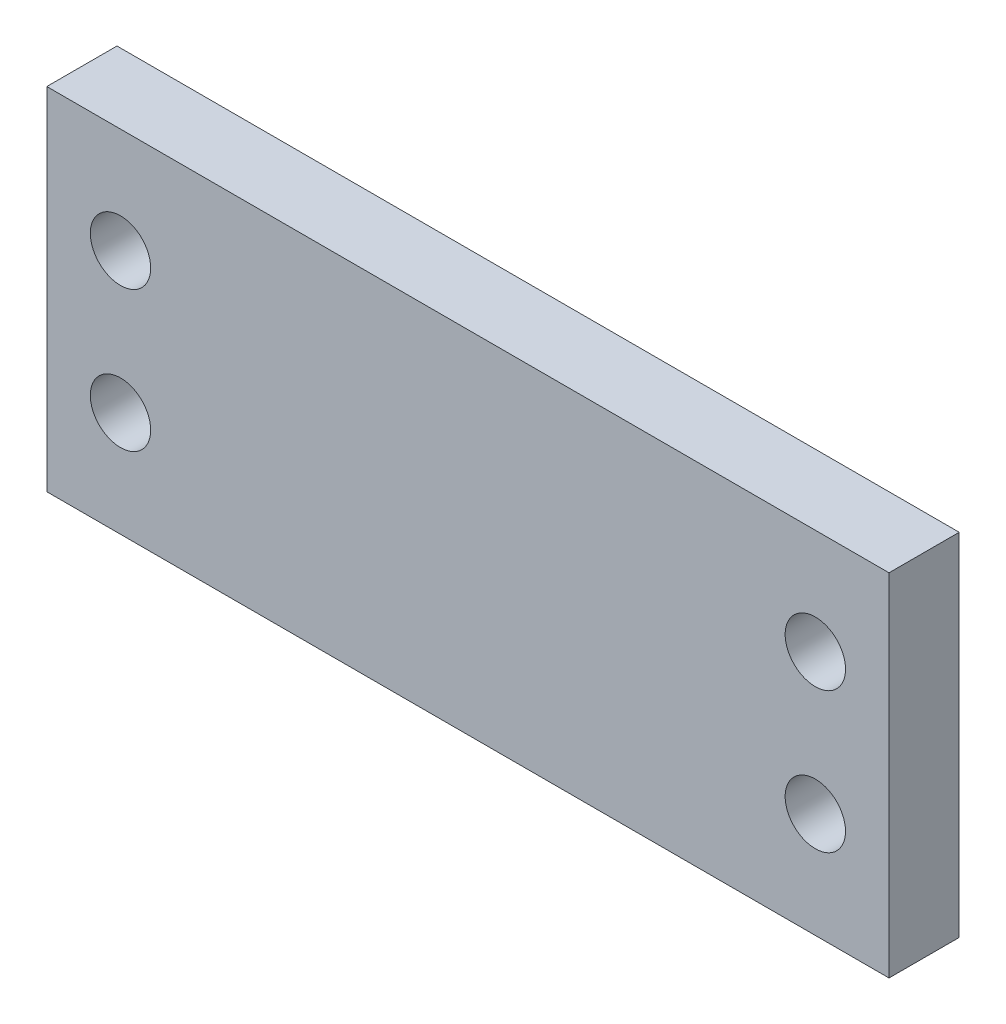
SolidWorks part; units mm, degrees
ref_plane "前视基准面" through (0, 0, 0) normal (0, 0, 1) x (1, 0, 0)
ref_plane "上视基准面" through (0, 0, 0) normal (0, 1, 0) x (1, 0, 0)
ref_plane "右视基准面" through (0, 0, 0) normal (1, 0, 0) x (0, 0, -1)
sketch "草图1" plane through (0, 0, 0) normal (0, 0, 1) x (1, 0, 0)
  line L1 (-30, 12.5) -> (30, 12.5)
  line L2 (-30, 12.5) -> (-30, -12.5)
  line L3 (-30, -12.5) -> (30, -12.5)
  line L4 (30, 12.5) -> (30, -12.5)
  line L5 (-30, 12.5) -> (30, -12.5) construction
  line L6 (-30, -12.5) -> (30, 12.5) construction
  point P0 (0, 0)
  dimension "D1" = 25
  dimension "D2" = 60
extrude "凸台-拉伸1" add sketch "草图1" along normal blind 5
sketch "草图2" plane through (0, 0, 5) normal (0, 0, 1) x (1, 0, 0)
  circle A0 centre (-24.75, 5) radius 2.15
  circle A1 centre (-24.75, -5) radius 2.15
  circle A2 centre (24.75, 5) radius 2.15
  circle A3 centre (24.75, -5) radius 2.15
extrude "切除-拉伸1" cut sketch "草图2" against normal blind 50
